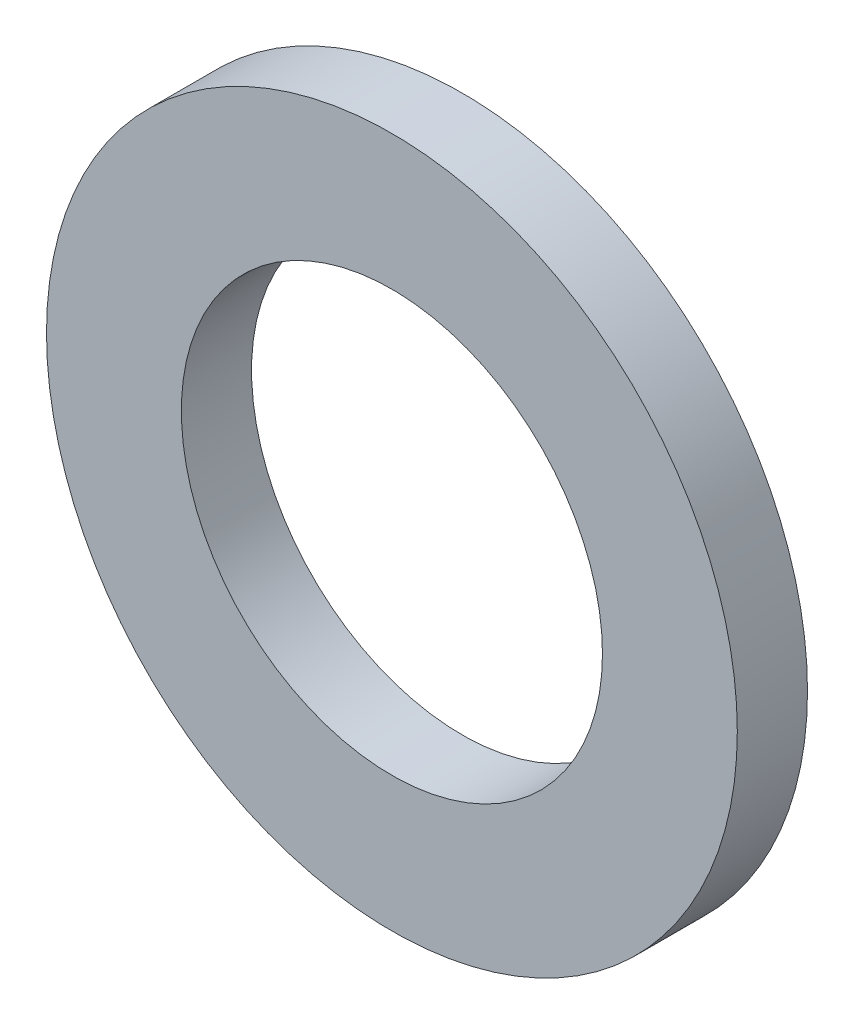
SolidWorks part; units mm, degrees
material "Rubber"
ref_plane "Front Plane" through (0, 0, 0) normal (0, 0, 1) x (1, 0, 0)
ref_plane "Top Plane" through (0, 0, 0) normal (0, 1, 0) x (1, 0, 0)
ref_plane "Right Plane" through (0, 0, 0) normal (1, 0, 0) x (0, 0, -1)
sketch "Sketch1" plane through (0, 0, 0) normal (0, 0, 1) x (1, 0, 0)
  circle A0 centre (0, 0) radius 1.524
  circle A1 centre (0, 0) radius 2.5
  dimension "ID" = 3.048
  dimension "OD" = 5
extrude "Extrude1" add sketch "Sketch1" against normal blind 0.508
